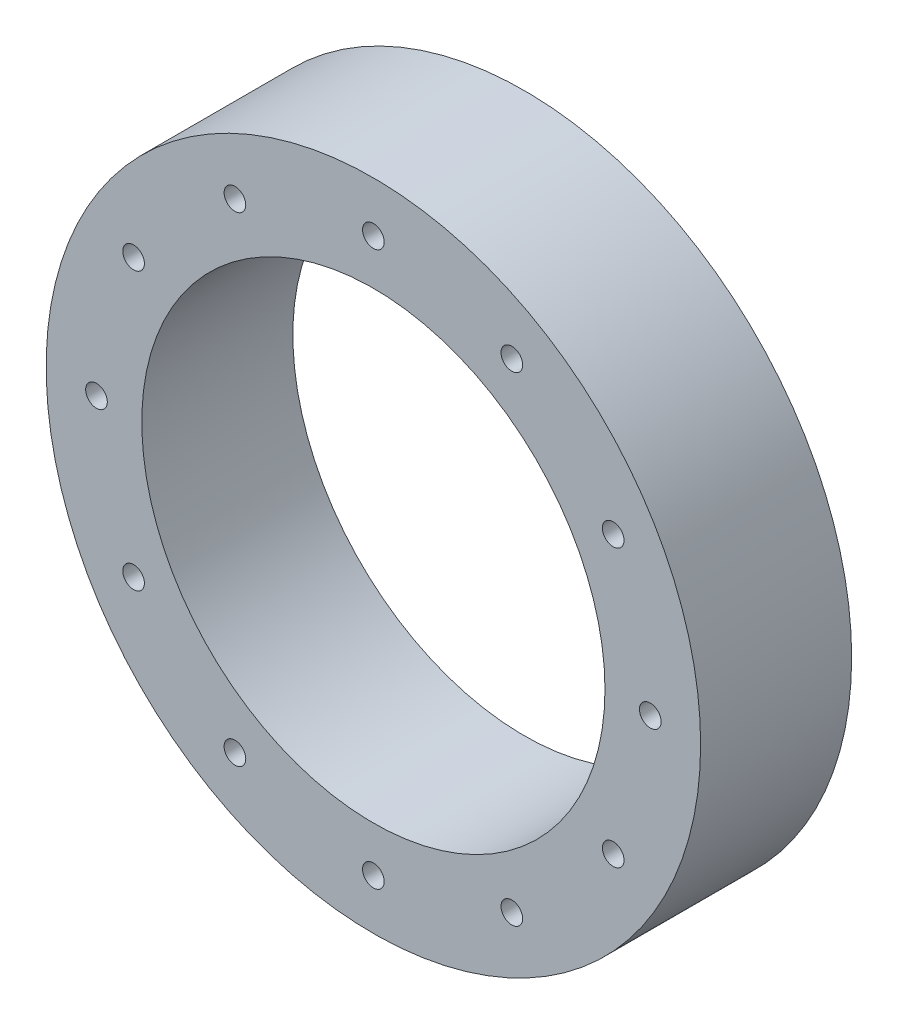
SolidWorks part; units mm, degrees
ref_plane "前视基准面" through (0, 0, 0) normal (0, 0, 1) x (1, 0, 0)
ref_plane "上视基准面" through (0, 0, 0) normal (0, 1, 0) x (1, 0, 0)
ref_plane "右视基准面" through (0, 0, 0) normal (1, 0, 0) x (0, 0, -1)
other "Configuration Table"
sketch "草图1" plane through (0, 0, 0) normal (0, 0, 1) x (1, 0, 0)
  circle A0 centre (0, 0) radius 46
  circle A1 centre (0, 0) radius 65
  circle A2 centre (0, 0) radius 55 construction
  circle A3 centre (0, 55) radius 2.15
  circle A4 centre (27.5, 47.6314) radius 2.15
  circle A5 centre (47.6314, 27.5) radius 2.15
  circle A6 centre (55, 0) radius 2.15
  circle A7 centre (47.6314, -27.5) radius 2.15
  circle A8 centre (27.5, -47.6314) radius 2.15
  circle A9 centre (0, -55) radius 2.15
  circle A10 centre (-27.5, -47.6314) radius 2.15
  circle A11 centre (-47.6314, -27.5) radius 2.15
  circle A12 centre (-55, 0) radius 2.15
  circle A13 centre (-47.6314, 27.5) radius 2.15
  circle A14 centre (-27.5, 47.6314) radius 2.15
  point P31 (0, 0)
  dimension "D1" = 92
  dimension "D2" = 130
  dimension "D3" = 110
  dimension "D4" = 4.3
  dimension "D5" = 12
extrude "凸台-拉伸1" add sketch "草图1" along normal blind 30
